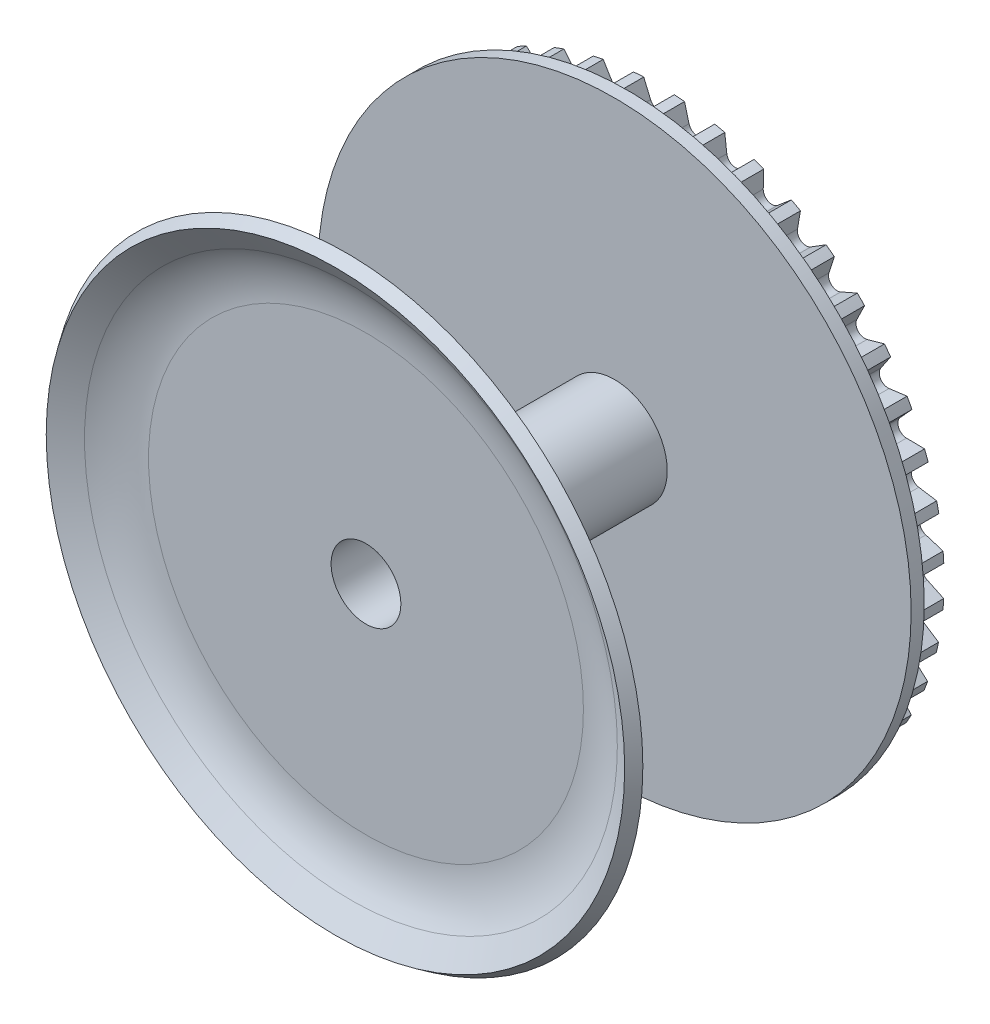
SolidWorks part; units mm, degrees
material "Nickel"
ref_plane "Front Plane" through (0, 0, 0) normal (0, 0, 1) x (1, 0, 0)
ref_plane "Top Plane" through (0, 0, 0) normal (0, 1, 0) x (1, 0, 0)
ref_plane "Right Plane" through (0, 0, 0) normal (1, 0, 0) x (0, 0, -1)
sketch "Sketch1" plane through (0, 0, 0) normal (1, 0, 0) x (0, 0, -1)
  line L0 (-87.5481, 0) -> (78.4594, 0) construction
  line L1 (-39.7343, 8) -> (-39.7343, 49.8547)
  line L2 (-43.185, 61.085) -> (-46.7343, 66.3155)
  line L3 (-46.7343, 66.3155) -> (-44.2519, 68)
  line L4 (-44.2519, 68) -> (-40.185, 62.0068)
  line L5 (-36.7343, 50.7765) -> (-36.7343, 12.0748)
  line L6 (-36.7343, 12.0748) -> (17.2657, 12.0748)
  line L7 (17.2657, 12.0748) -> (17.2657, 68)
  line L8 (17.2657, 68) -> (20.2657, 68)
  line L9 (20.2657, 68) -> (20.2657, 65.5651)
  line L10 (21.2657, 65.5651) -> (27.2657, 65.5651)
  line L11 (27.2657, 65.5651) -> (27.2657, 8)
  line L12 (20.2657, 65.5651) -> (20.2657, 17.9732)
  line L13 (20.2657, 17.9732) -> (21.2657, 17.9732)
  line L14 (21.2657, 17.9732) -> (21.2657, 65.5651)
  line L15 (-39.7343, 8) -> (27.2657, 8)
  arc A0 (-40.185, 62.0068) -> (-36.7343, 50.7765) centre (-56.7343, 50.7765) cw
  arc A1 (-39.7343, 49.8547) -> (-43.185, 61.085) centre (-59.7343, 49.8547) ccw
  dimension "D2" = 20
  dimension "D1" = 68
  dimension "D3" = 3
  dimension "D4" = 3
  dimension "D5" = 54
  dimension "D6" = 74
  dimension "D7" = 7
  dimension "D8" = 3
  dimension "D9" = 1
  dimension "D10" = 16
revolve "Revolve1" add sketch "Sketch1" angle 360 about L0
sketch "Sketch2" plane through (0, 0, -27.2657) normal (0, 0, -1) x (-1, 0, 0)
  line L0 (0, 0) -> (0, 65.5651) construction
  line L1 (-3.6854, 65.4615) -> (-1.906, 61.7097)
  line L2 (1.7414, 61.7837) -> (3.3146, 65.4813)
  line L3 (-3.6854, 65.4615) -> (-0.317, 66.2407)
  line L4 (-0.317, 66.2407) -> (3.3146, 65.4813)
  circle A0 centre (0, 0) radius 65.5651 construction
  arc A1 (-1.906, 61.7097) -> (1.7414, 61.7837) centre (-0.0989, 62.5667) ccw
  point P10 (0, 57.6909)
  dimension "D2" = 2
  dimension "D3" = 3
  dimension "D1" = 7
extrude "Cut-Extrude1" cut sketch "Sketch2" against normal blind 6
pattern_circular "CirPattern1" count 44 over 360 about axis through (0, 0, 0) along (0, 0, 1) of "Cut-Extrude1"
